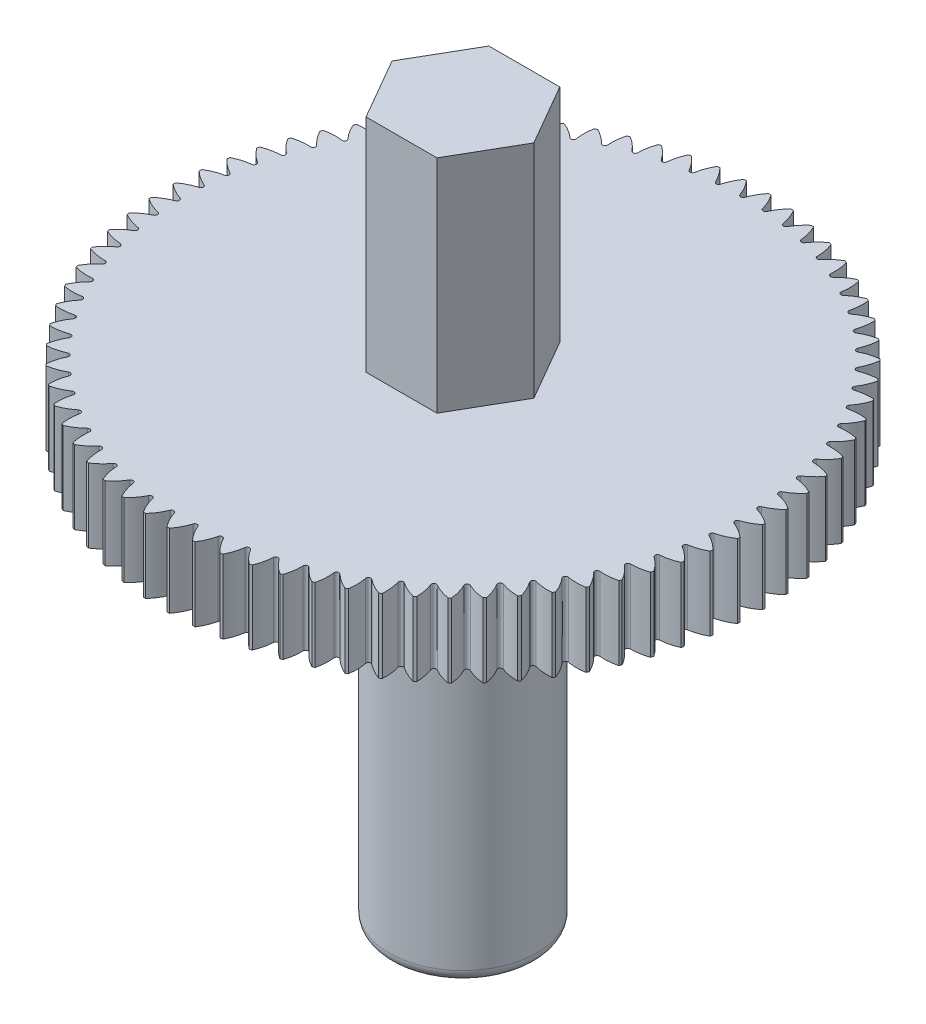
SolidWorks part; units mm, degrees
ref_plane "Front Plane" through (0, 0, 0) normal (0, 0, 1) x (1, 0, 0)
ref_plane "Top Plane" through (0, 0, 0) normal (0, 1, 0) x (1, 0, 0)
ref_plane "Right Plane" through (0, 0, 0) normal (1, 0, 0) x (0, 0, -1)
sketch "Sketch2" plane through (0, 0, 0) normal (1, 0, 0) x (0, 0, -1)
  line L0 (0, 0) -> (0, 29)
  line L1 (0, 55) -> (0, -55) construction
  line L2 (0, 0) -> (3, 0)
  line L3 (55, 0) -> (-55, 0) construction
  line L4 (3, 0) -> (3, 17)
  line L5 (3, 17) -> (12, 17)
  line L6 (12, 17) -> (12, 20)
  line L7 (12, 20) -> (3, 20)
  line L8 (3, 20) -> (3, 29)
  line L9 (0, 29) -> (3, 29)
  dimension "D1" = 29
  dimension "D2" = 3
  dimension "D3" = 17
  dimension "D4" = 3
  dimension "D5" = 9
  dimension "D6" = 9
revolve "Revolve1" add sketch "Sketch2" angle 360 about L0
fillet "Fillet1" radius 0.5 1 edges at (0, 0, -3)
sketch "Sketch7" plane through (0, 29, 0) normal (0, 1, 0) x (1, 0, 0)
  line L1 (1.4434, -2.5) -> (2.8868, 0)
  line L2 (2.8868, 0) -> (1.4434, 2.5)
  line L3 (1.4434, 2.5) -> (-1.4434, 2.5)
  line L4 (-1.4434, 2.5) -> (-2.8868, 0)
  line L5 (-2.8868, 0) -> (-1.4434, -2.5)
  line L6 (-1.4434, -2.5) -> (1.4434, -2.5)
  circle A0 centre (0, 0) radius 3 construction
  circle A1 centre (0, 0) radius 3
  circle A2 centre (0, 0) radius 2.5 construction
  point P3 (-10.7027, 0.2847)
  dimension "D2" = 2.8868
extrude "Cut-Extrude5" cut sketch "Sketch7" against normal blind 9
sketch "Sketch12" plane through (0, 20, 0) normal (0, 1, 0) x (1, 0, 0)
  line L0 (0, 0) -> (0, 16.7272) construction
  circle A0 centre (0, 0) radius 12 construction
  circle A1 centre (0, 0) radius 12
  arc A2 (-0.45, 11.9916) -> (-0.0942, 11.3714) centre (-1.979, 10.7023) cw
  arc A3 (0.0942, 11.3714) -> (0.45, 11.9916) centre (1.979, 10.7023) cw
  arc A4 (-0.0942, 11.3714) -> (0.0942, 11.3714) centre (0, 11.4049) ccw
  point P11 (0, 10.9916)
  circle M3 centre (0, 0) radius 12
  dimension "D3" = 2
  dimension "D4" = 2
  dimension "D5" = 0.1
  dimension "D1" = 0.9
  dimension "D2" = 1
extrude "Cut-Extrude7" cut sketch "Sketch12" against normal blind 4 contours A4 L0 A2 M3 | L0 A4 A3 A1
pattern_circular "CirPattern2" count 75 over 360 about axis through (0, 0, 0) along (0, 1, 0) of "Cut-Extrude7"
